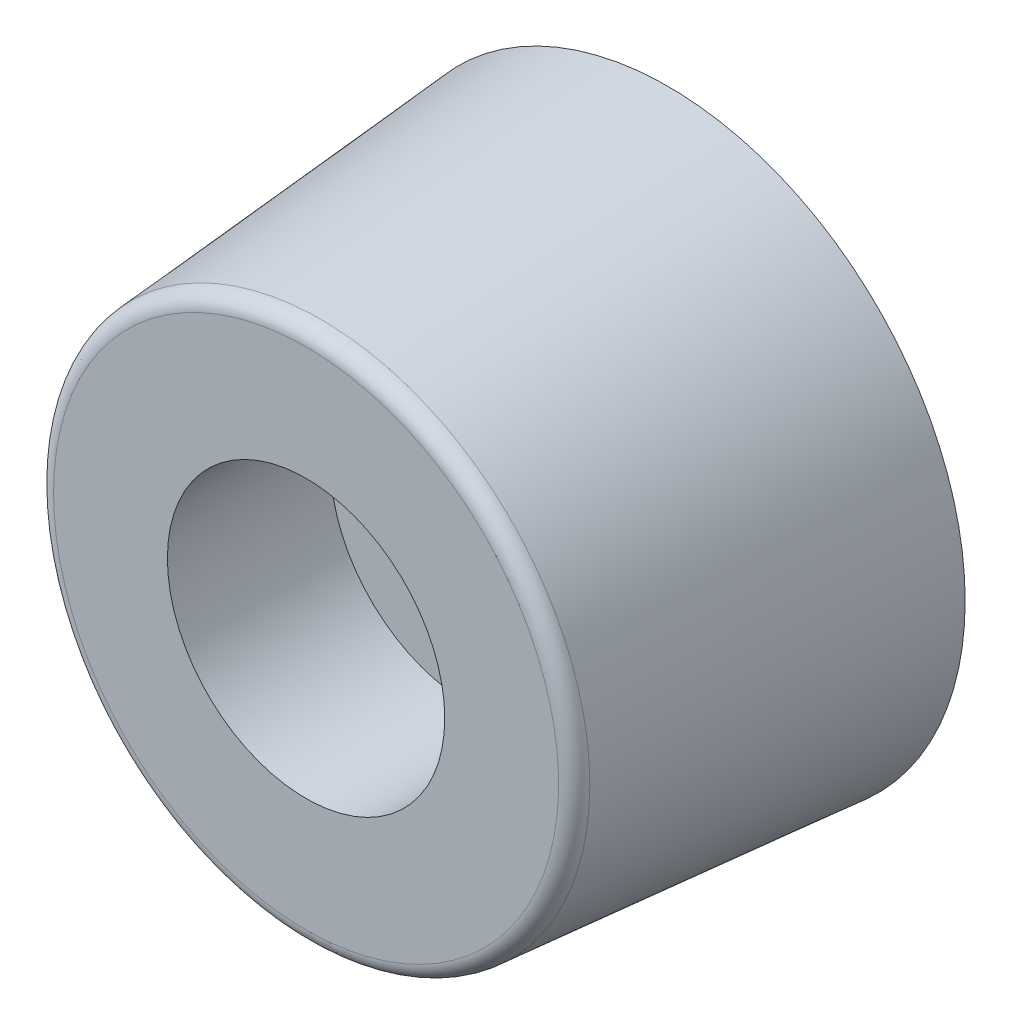
SolidWorks part; units mm, degrees
material "EPDM 60 Durometer"
ref_plane "Front Plane" through (0, 0, 0) normal (0, 0, 1) x (1, 0, 0)
ref_plane "Top Plane" through (0, 0, 0) normal (0, 1, 0) x (1, 0, 0)
ref_plane "Right Plane" through (0, 0, 0) normal (1, 0, 0) x (0, 0, -1)
sketch "Sketch1" plane through (0, 0, 0) normal (1, 0, 0) x (0, 0, -1)
  line L0 (0, 0) -> (-15.6478, 0) construction
  line L1 (0, 2.45) -> (0, 4.25)
  line L2 (0, 4.25) -> (-5, 4.25)
  line L3 (-5, 4.25) -> (-5, 7.7389)
  line L4 (-4.5404, 8.2373) -> (6.1, 9.1)
  line L5 (6.1, 9.1) -> (6.1, 2.85)
  line L6 (6.1, 0) -> (0, 0) construction
  line L7 (3.8, 2.85) -> (6.1, 2.85)
  line L8 (0, 2.45) -> (3.8, 2.45)
  line L9 (3.8, 2.45) -> (3.8, 2.85)
  line L10 (0, 0) -> (0, 2.45) construction
  line L11 (6.1, 2.85) -> (6.1, 0) construction
  arc A0 (-5, 7.7389) -> (-4.5404, 8.2373) centre (-4.5, 7.7389) cw
  point P14 (-5, 8.2)
  dimension "D9" = 0.5
  dimension "D1" = 18.2
  dimension "D2" = 8.5
  dimension "D3" = 16.4
  dimension "D4" = 11.1
  dimension "D5" = 5
  dimension "D6" = 5.7
  dimension "D7" = 4.9
  dimension "D8" = 2.3
revolve "Revolve1" add sketch "Sketch1" angle 360 about L0
